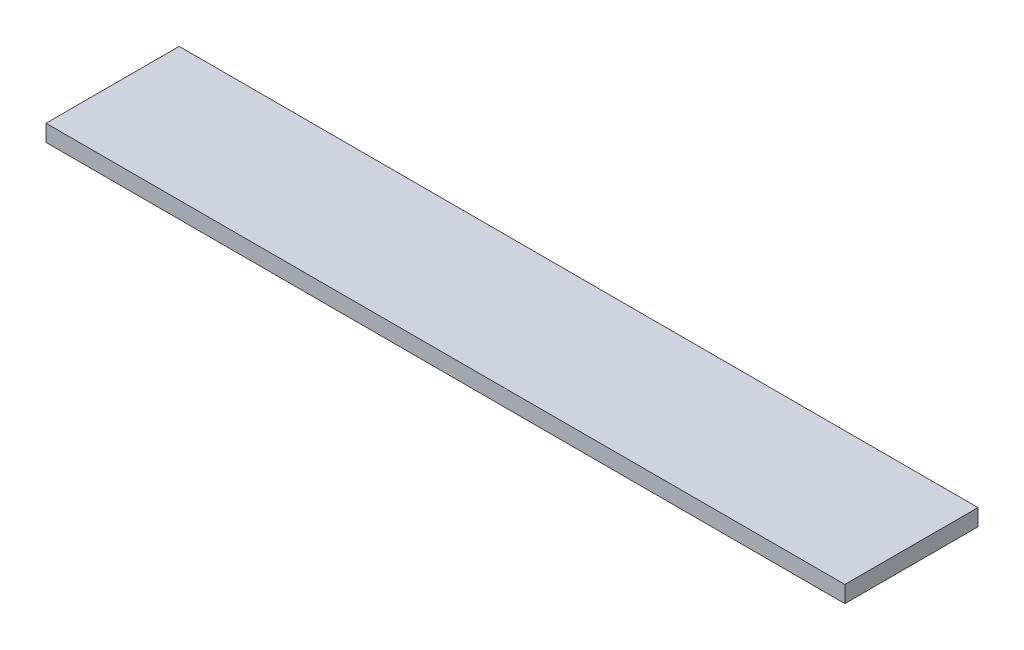
SolidWorks part; units mm, degrees
material "Polyurethane Foam Flexible"
ref_plane "Front Plane" through (0, 0, 0) normal (0, 0, 1) x (1, 0, 0)
ref_plane "Top Plane" through (0, 0, 0) normal (0, 1, 0) x (1, 0, 0)
ref_plane "Right Plane" through (0, 0, 0) normal (1, 0, 0) x (0, 0, -1)
sketch "Sketch1" plane through (0, 0, 0) normal (0, 1, 0) x (1, 0, 0)
  line L1 (-76.2, -12.7) -> (76.2, -12.7)
  line L2 (-76.2, -12.7) -> (-76.2, 12.7)
  line L3 (-76.2, 12.7) -> (76.2, 12.7)
  line L4 (76.2, -12.7) -> (76.2, 12.7)
  line L5 (-76.2, -12.7) -> (76.2, 12.7) construction
  line L6 (-76.2, 12.7) -> (76.2, -12.7) construction
  point P0 (0, 0)
  dimension "D1" = 25.4
  dimension "D2" = 152.4
extrude "Boss-Extrude1" add sketch "Sketch1" along normal blind 3.175
